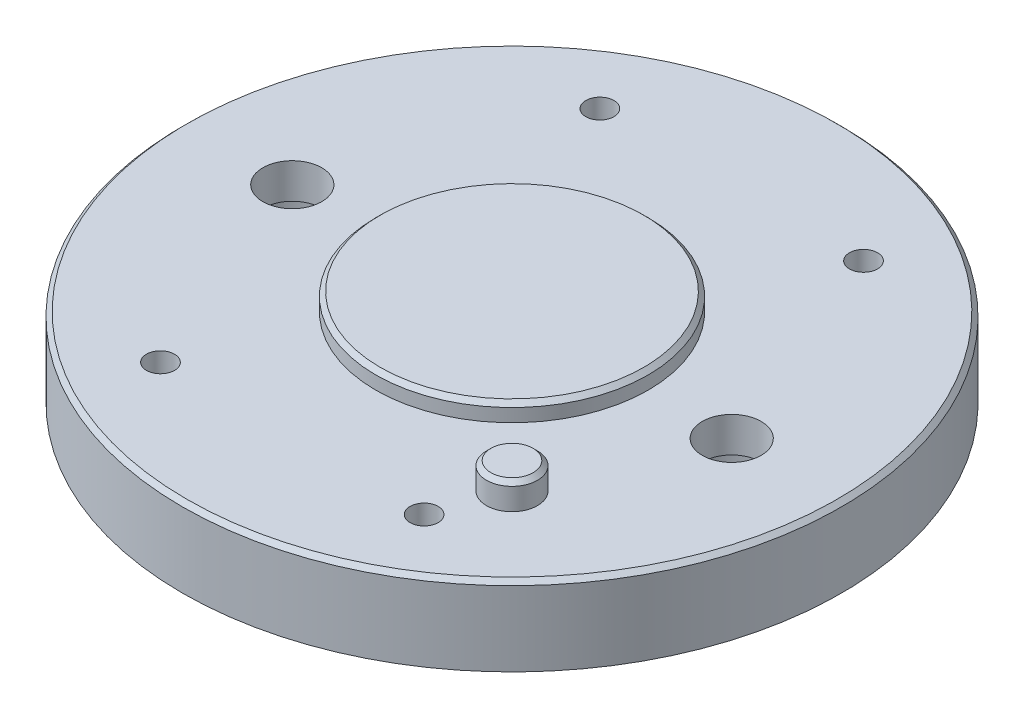
SolidWorks part; units mm, degrees
ref_plane "Ebene vorne" through (0, 0, 0) normal (0, 0, 1) x (1, 0, 0)
ref_plane "Ebene oben" through (0, 0, 0) normal (0, 1, 0) x (1, 0, 0)
ref_plane "Ebene rechts" through (0, 0, 0) normal (1, 0, 0) x (0, 0, -1)
sketch "Skizze1" plane through (0, 0, 0) normal (0, 1, 0) x (1, 0, 0)
  circle A0 centre (0, 0) radius 37.5
  circle A2 centre (-25, 0) radius 3.25
  circle A3 centre (25, 0) radius 3.25
  dimension "D1" = 75
  dimension "D2" = 6.5
  dimension "D3" = 50
  dimension "D4" = 25
extrude "Aufsatz-Linear austragen1" add sketch "Skizze1" along normal blind 9
hole_wizard "Bohrung1" positions "3D-Skizze1" profile "Skizze2" legacy end condition through all
sketch3d "3D-Skizze1"
  line L0 (25, 9, 0) -> (25, 0, 0) construction
  line L1 (-25, 9, 0) -> (-25, 0, 0) construction
  point P0 (25, 0, 0)
  point P4 (-25, 0, 0)
sketch "Skizze2" plane through (25, 0, 0) normal (1, 0, 0) x (0, 0, -1)
  line L0 (0, 0) -> (0, 9)
  line L1 (0, 9) -> (3.35, 9)
  line L2 (3.35, 9) -> (3.35, 5)
  line L3 (3.35, 5) -> (5.55, 5)
  line L4 (5.55, 5) -> (5.55, 0)
  line L5 (5.55, 0) -> (0, 0)
  line L6 (0, 110) -> (0, -10) construction
  dimension "Durchmesser" = 6.7
  dimension "Tiefe" = 9
  dimension "Senkdurchmesser1" = 11.1
  dimension "Senktiefe1" = 5
sketch "Skizze3" plane through (0, 9, 0) normal (0, 1, 0) x (-1, 0, 0)
  circle A2 centre (0, 0) radius 15.5
  dimension "D2" = 31
sketch "Skizze5" plane through (0, 9, 0) normal (0, 1, 0) x (-1, 0, 0)
  line L0 (0, 0) -> (-35.4628, 0) construction
  line L1 (0, 0) -> (-17.6777, 17.6777) construction
  circle A0 centre (0, 0) radius 25 construction
  circle A1 centre (-17.6777, 17.6777) radius 2.9
  dimension "D1" = 45
  dimension "D2" = 5.8
extrude "Aufsatz-Linear austragen2" add sketch "Skizze3" along normal blind 2 contours A2
chamfer "Fase1" distance 0.5 angle 45 1 edges at (0, 11, 15.5)
sketch "Skizze6" plane through (0, 0, 0) normal (0, -1, 0) x (1, 0, 0)
  line L5 (-25, 30) -> (25, 30) construction
  line L6 (-25, 30) -> (-25, -30) construction
  line L7 (-25, -30) -> (25, -30) construction
  line L8 (25, 30) -> (25, -30) construction
  dimension "D1" = 50
  dimension "D2" = 25
  dimension "D3" = 30
  dimension "D4" = 60
sketch "Skizze7" plane through (0, 0, 0) normal (0, -1, 0) x (-1, 0, 0)
  line L0 (25, -30) -> (-25, -30) construction
  line L1 (15, -25) -> (-15, -25) construction
  line L2 (15, -25) -> (15, 25) construction
  line L3 (15, 25) -> (-15, 25) construction
  line L4 (-15, -25) -> (-15, 25) construction
  line L5 (-25, -30) -> (-25, 30) construction
  line L7 (25, -30) -> (25, 30) construction
  line L8 (25, 30) -> (-25, 30) construction
  circle A0 centre (-15, 25) radius 1.6
  circle A1 centre (15, 25) radius 1.6
  circle A2 centre (15, -25) radius 1.6
  circle A3 centre (-15, -25) radius 1.6
  dimension "D5" = 3.2
  dimension "D8" = 30
  dimension "D9" = 30
  dimension "D1" = 10
  dimension "D2" = 10
  dimension "D3" = 5
  dimension "D4" = 5
  dimension "D6" = 15
  dimension "D7" = 25
extrude "Schnitt-Linear austragen2" cut sketch "Skizze7" against normal through all contours A0 | A1 | A2 | A3
chamfer "Fase2" distance 0.5 angle 45 1 edges at (0, 9, 37.5)
extrude "Aufsatz-Linear austragen3" add sketch "Skizze5" along normal blind 3
chamfer "Fase4" distance 0.5 angle 45 1 edges at (17.6777, 12, 20.5777)
equation "\"7.5.00mm\"=9"
